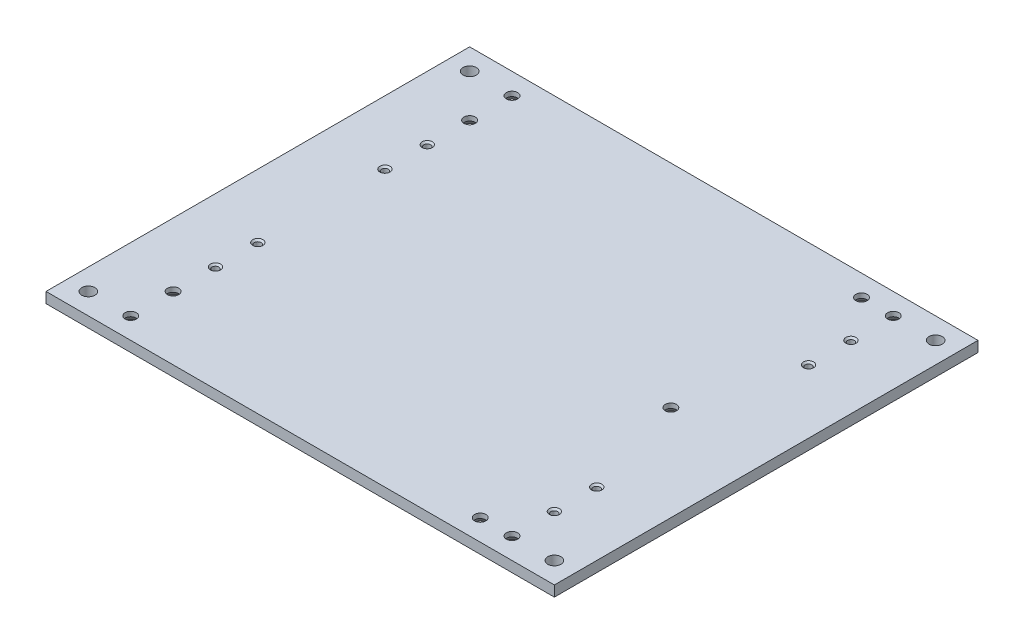
SolidWorks part; units mm, degrees
ref_plane "Front Plane" through (0, 0, 0) normal (0, 0, 1) x (1, 0, 0)
ref_plane "Top Plane" through (0, 0, 0) normal (0, 1, 0) x (1, 0, 0)
ref_plane "Right Plane" through (0, 0, 0) normal (1, 0, 0) x (0, 0, -1)
sketch "Sketch2" plane through (0, 0, 0) normal (0, 1, 0) x (1, 0, 0)
  line L1 (152.4, -127) -> (-152.4, -127)
  line L2 (152.4, -127) -> (152.4, 127)
  line L3 (152.4, 127) -> (-152.4, 127)
  line L4 (-152.4, -127) -> (-152.4, 127)
  line L5 (152.4, -127) -> (-152.4, 127) construction
  line L6 (152.4, 127) -> (-152.4, -127) construction
  point P0 (0, 0)
  dimension "D1" = 304.8
  dimension "D2" = 254
extrude "Boss-Extrude1" add sketch "Sketch2" along normal blind 6.35
sketch "Sketch3" plane through (0, 6.35, 0) normal (0, 1, 0) x (1, 0, 0)
  line L0 (152.4, -127) -> (152.4, 127) construction
  line L1 (152.4, 127) -> (-152.4, 127) construction
  line L2 (-152.4, -127) -> (152.4, -127) construction
  line L4 (-152.4, 127) -> (-152.4, -127) construction
  circle A0 centre (139.7, 114.3) radius 3.9687
  circle A1 centre (139.7, -114.3) radius 3.9687
  circle A2 centre (-139.7, 114.3) radius 3.9687
  circle A3 centre (-139.7, -114.3) radius 3.9687
  dimension "D1" = 7.9375
  dimension "D2" = 12.7
  dimension "D3" = 12.7
  dimension "D4" = 12.7
  dimension "D5" = 12.7
  dimension "D6" = 12.7
  dimension "D7" = 12.7
  dimension "D8" = 12.7
  dimension "D9" = 12.7
extrude "Cut-Extrude1" cut sketch "Sketch3" against normal through all
hole_wizard "CSK for 1/4 Flat Head Machine Screw1" positions "Sketch4" profile "Sketch5" countersink size "1/4" standard "ANSI Inch" end condition through all
sketch "Sketch4" plane through (0, 0, 0) normal (0, -1, 0) x (-1, 0, 0)
  line L0 (152.4, -127) -> (-152.4, -127) construction
  line L1 (-152.4, 127) -> (152.4, 127) construction
  line L2 (-152.4, 127) -> (152.4, 127) construction
  circle A0 centre (-139.7, -114.3) radius 3.9687 construction
  circle A1 centre (-139.7, 114.3) radius 3.9687 construction
  circle A2 centre (139.7, -114.3) radius 3.9687 construction
  circle A3 centre (139.7, 114.3) radius 3.9687 construction
  circle A4 centre (139.7, -114.3) radius 3.9687 construction
  circle A5 centre (139.7, 114.3) radius 3.9687 construction
  point P0 (114.3, 114.3)
  point P2 (114.3, -114.3)
  point P4 (-114.3, -114.3)
  point P6 (-114.3, 114.3)
  point P8 (-95.25, 114.3)
  point P10 (-95.25, 0)
  point P12 (-95.25, -114.3)
  point P29 (114.3, 88.9)
  point P31 (114.3, -88.9)
  dimension "D1" = 12.7
  dimension "D2" = 12.7
  dimension "D3" = 12.7
  dimension "D4" = 25.4
  dimension "D5" = 12.7
  dimension "D6" = 12.7
  dimension "D7" = 25.4
  dimension "D8" = 19.05
  dimension "D9" = 19.05
  dimension "D10" = 25.4
  dimension "D11" = 25.4
  dimension "D12" = 127
  dimension "D13" = 19.05
  dimension "D14" = 12.7
  dimension "D15" = 25.4
  dimension "D16" = 25.4
  dimension "D17" = 25.4
  dimension "D18" = 25.4
sketch "Sketch5" plane through (-114.3, 0, -114.3) normal (1, 0, 0) x (0, 0, -1)
  line L0 (0, 0) -> (0, 6.35)
  line L1 (0, 6.35) -> (3.3782, 6.35)
  line L2 (3.3782, 6.35) -> (3.3782, 3.5209)
  line L3 (3.3782, 3.5209) -> (6.4389, 0)
  line L5 (6.4389, 0) -> (0, 0)
  line L6 (-3.3782, 3.5209) -> (-6.4389, 0) construction
  line L11 (0, -6.35) -> (0, 107.95) construction
  dimension "Thru Hole Dia." = 6.7564
  dimension "Thru Hole Depth" = 6.35
  dimension "Near C'Sink Dia." = 12.8778
  dimension "Near C'Sink Angle" = 82
hole_wizard "#10-32 Tapped Hole1" positions "Sketch6" profile "Sketch7" tap size "#10-32" standard "ANSI Inch" end condition through all
sketch "Sketch6" plane through (0, 6.35, 0) normal (0, 1, 0) x (1, 0, 0)
  line L0 (152.4, -127) -> (152.4, 127) construction
  circle A0 centre (114.3, -114.3) radius 3.3782 construction
  circle A1 centre (114.3, 114.3) radius 3.3782 construction
  circle A4 centre (-139.7, -114.3) radius 3.9687 construction
  circle A5 centre (-114.3, -88.9) radius 3.3782 construction
  circle A6 centre (-139.7, 114.3) radius 3.9687 construction
  circle A7 centre (-114.3, 88.9) radius 3.3782 construction
  point P0 (114.3, -88.9)
  point P2 (114.3, -63.5)
  point P4 (114.3, 63.5)
  point P6 (114.3, 88.9)
  point P8 (-114.3, 63.5)
  point P10 (-114.3, 38.1)
  point P12 (-114.3, -63.5)
  point P14 (-114.3, -38.1)
  dimension "D1" = 25.4
  dimension "D2" = 25.4
  dimension "D3" = 25.4
  dimension "D4" = 25.4
  dimension "D5" = 25.4
  dimension "D6" = 25.4
  dimension "D7" = 25.4
  dimension "D8" = 25.4
  dimension "D9" = 25.4
  dimension "D10" = 25.4
  dimension "D11" = 25.4
  dimension "D12" = 25.4
  dimension "D13" = 38.1
  dimension "D14" = 38.1
sketch "Sketch7" plane through (114.3, 6.35, 88.9) normal (1, 0, 0) x (0, 0, 1)
  line L0 (0, 0) -> (0, 6.35)
  line L1 (0, 6.35) -> (2.0193, 6.35)
  line L2 (2.0193, 6.35) -> (2.0193, 1.0287)
  line L3 (2.0193, 1.0287) -> (3.048, 0)
  line L5 (3.048, 0) -> (0, 0)
  line L6 (-2.0193, 1.0287) -> (-3.048, 0) construction
  line L11 (0, -6.35) -> (0, 107.95) construction
  dimension "Thru Tap Drill Dia." = 4.0386
  dimension "Thru Tap Drill Depth" = 6.35
  dimension "Near C'Sink Dia." = 6.096
  dimension "Near C'Sink Angle" = 90
cosmetic thread "Hole Thread1" parameters "D2"=4.826
cosmetic thread "Hole Thread3" parameters "D2"=4.826
cosmetic thread "Hole Thread5" parameters "D2"=4.826
cosmetic thread "Hole Thread6" parameters "D2"=4.826
cosmetic thread "Hole Thread7" parameters "D2"=4.826
cosmetic thread "Hole Thread8" parameters "D2"=4.826
cosmetic thread "Hole Thread9" parameters "D2"=4.826
cosmetic thread "Hole Thread10" parameters "D2"=4.826
